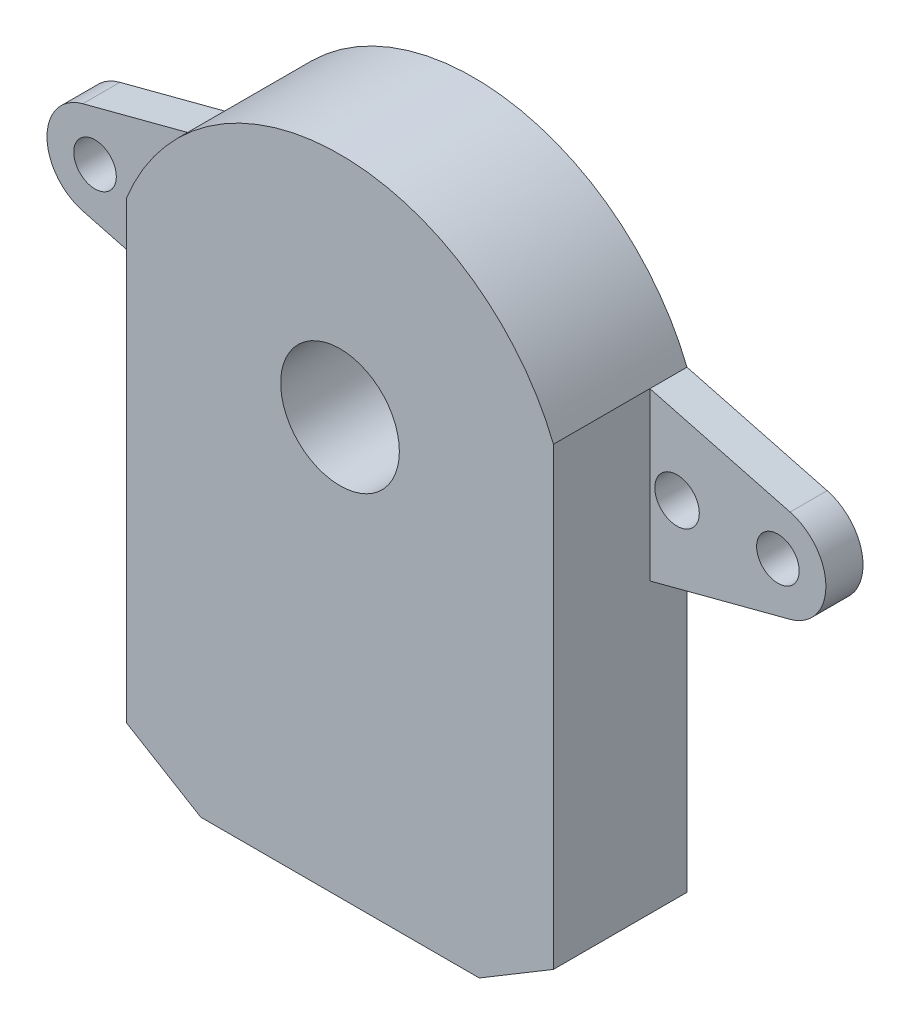
SolidWorks part; units mm, degrees
ref_plane "正面" through (0, 0, 0) normal (0, 0, 1) x (1, 0, 0)
ref_plane "平面" through (0, 0, 0) normal (0, 1, 0) x (1, 0, 0)
ref_plane "右側面" through (0, 0, 0) normal (1, 0, 0) x (0, 0, -1)
sketch "ｽｹｯﾁ1" plane through (0, 0, 0) normal (0, 0, 1) x (1, 0, 0)
  line L0 (0, 0) -> (0, -0.16) construction
  line L1 (23.0125, 0) -> (-23.0125, 0) construction
  line L2 (14.385, -28.04) -> (-14.385, -28.04)
  line L3 (14.385, -28.04) -> (14.385, -5.6125)
  line L5 (-14.385, -28.04) -> (-14.385, -5.6125)
  line L6 (14.385, -28.04) -> (-14.385, 5.6125) construction
  line L7 (14.385, 5.6125) -> (-14.385, -28.04) construction
  line L8 (-14.385, 5.6125) -> (-23.8347, 3.1314)
  line L9 (-23.8347, -3.1314) -> (-14.385, -5.6125)
  line L10 (23.8347, -3.1314) -> (14.385, -5.6125)
  line L11 (14.385, 5.6125) -> (23.8347, 3.1314)
  circle A0 centre (0, 0) radius 4
  circle A2 centre (-23.0125, 0) radius 1.435
  circle A3 centre (23.0125, 0) radius 1.435
  arc A4 (-23.8347, 3.1314) -> (-23.8347, -3.1314) centre (-23.0125, 0) ccw
  arc A5 (23.8347, 3.1314) -> (23.8347, -3.1314) centre (23.0125, 0) cw
  arc A6 (14.385, 5.6125) -> (-14.385, 5.6125) centre (0, -0.16) ccw
  circle A7 centre (-16.215, 0) radius 1.5
  circle A8 centre (16.215, 0) radius 1.5
  point P4 (-26.25, 0)
  point P5 (0, -11.2137)
  point P12 (0, 0)
  point P16 (26.25, 0)
  point P26 (0, 15.34)
  dimension "D1" = 8
  dimension "D2" = 28.77
  dimension "D3" = 15.5
  dimension "D5" = 2.87
  dimension "D6" = 0.16
  dimension "D9" = 3
  dimension "D10" = 32.43
  dimension "D4" = 28.77
  dimension "D7" = 43.38
  dimension "D8" = 46.025
  dimension "D11" = 52.5
extrude "ﾎﾞｽ - 押し出し1" add sketch "ｽｹｯﾁ1" along normal blind 9
sketch "ｽｹｯﾁ2" plane through (0, 0, 9) normal (0, 0, 1) x (1, 0, 0)
  line L7 (-14.385, 5.6125) -> (-23.8347, 3.1314)
  line L8 (-23.8347, -3.1314) -> (-14.385, -5.6125)
  line L9 (-14.385, -5.6125) -> (-14.385, -28.04)
  line L10 (-14.385, -28.04) -> (14.385, -28.04)
  line L11 (14.385, -28.04) -> (14.385, -5.6125)
  line L12 (14.385, -5.6125) -> (23.8347, -3.1314)
  line L13 (23.8347, 3.1314) -> (14.385, 5.6125)
  line L14 (-14.385, 5.6125) -> (-23.8347, 3.1314)
  line L15 (-23.8347, -3.1314) -> (-14.385, -5.6125)
  line L16 (-14.385, 5.6125) -> (-14.385, -5.6125)
  line L18 (14.385, -5.6125) -> (14.385, 5.6125)
  line L19 (14.385, -5.6125) -> (23.8347, -3.1314)
  line L20 (23.8347, 3.1314) -> (14.385, 5.6125)
  arc A3 (14.385, 5.6125) -> (-14.385, 5.6125) centre (0, -0.16) ccw
  arc A4 (-23.8347, 3.1314) -> (-23.8347, -3.1314) centre (-23.0125, 0) ccw
  arc A5 (23.8347, -3.1314) -> (23.8347, 3.1314) centre (23.0125, 0) ccw
  arc A7 (-23.8347, 3.1314) -> (-23.8347, -3.1314) centre (-23.0125, 0) ccw
  arc A8 (23.8347, -3.1314) -> (23.8347, 3.1314) centre (23.0125, 0) ccw
  dimension "D1" = 0
extrude "ｶｯﾄ - 押し出し1" cut sketch "ｽｹｯﾁ2" against normal blind 6.5
chamfer "面取り1" distance 5 distance2 3 1 edges at (14.385, -28.04, 4.5)
chamfer "面取り2" distance 3 distance2 5 1 edges at (-14.385, -28.04, 4.5)
